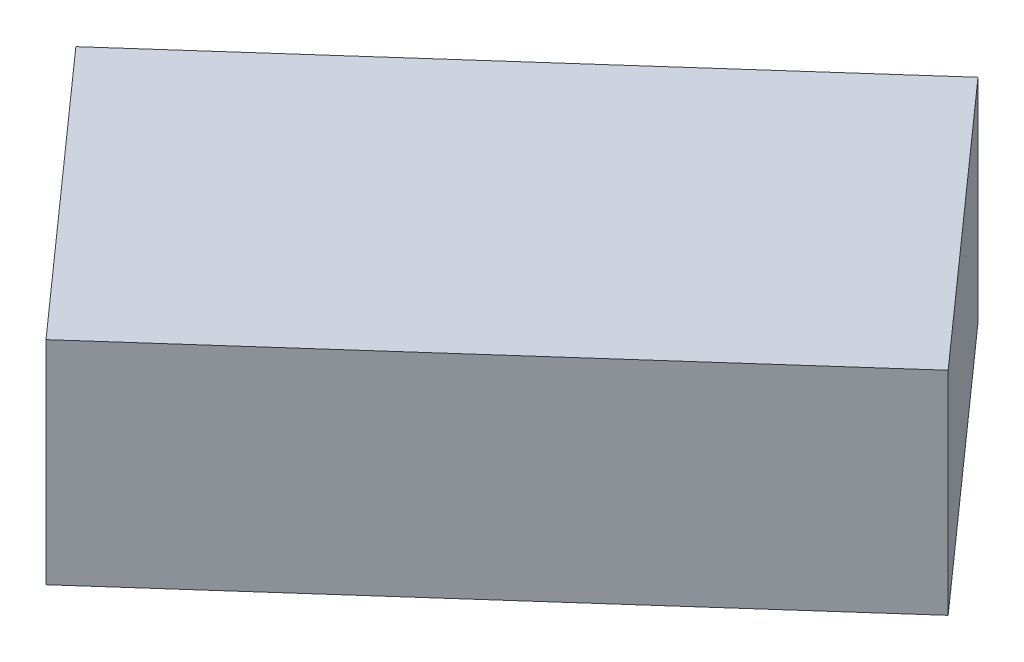
SolidWorks part; units mm, degrees
ref_plane "前视基准面" through (0, 0, 0) normal (0, 0, 1) x (1, 0, 0)
ref_plane "上视基准面" through (0, 0, 0) normal (0, 1, 0) x (1, 0, 0)
ref_plane "右视基准面" through (0, 0, 0) normal (1, 0, 0) x (0, 0, -1)
other "Configuration Table"
sketch "草图1" plane through (0, 0, 0) normal (0, 1, 0) x (1, 0, 0)
  line L0 (104.32, -54.86) -> (122.32, -38.86)
  line L1 (122.32, -38.86) -> (113.32, -28.735)
  line L2 (113.32, -28.735) -> (95.32, -44.735)
  line L3 (95.32, -44.735) -> (104.32, -54.86)
extrude "凸台-拉伸1" add sketch "草图1" along normal blind 8 from offset 4
sketch "草图2" plane through (0, 0, 0) normal (0, 1, 0) x (1, 0, 0)
  line L0 (95.32, -44.735) -> (104.32, -54.86) construction
  circle A0 centre (100, -50) radius 3
  circle A1 centre (114, -38) radius 1.5
extrude "切除-拉伸1" cut sketch "草图2" against normal through all
